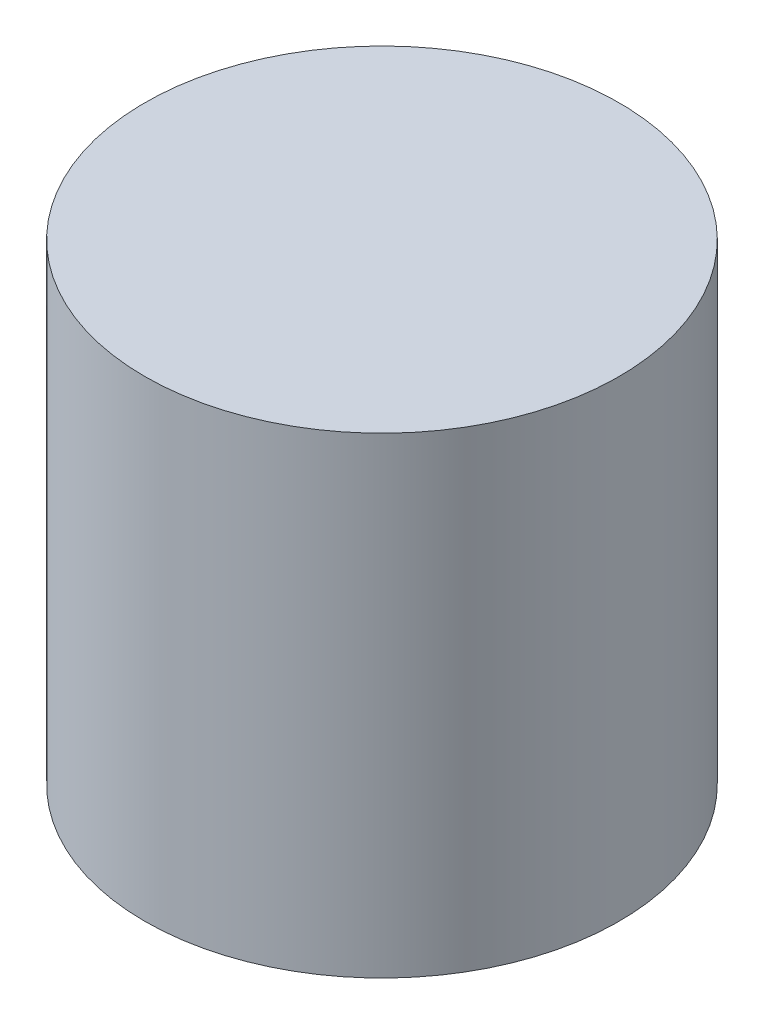
SolidWorks part; units mm, degrees
ref_plane "Front Plane" through (0, 0, 0) normal (0, 0, 1) x (1, 0, 0)
ref_plane "Top Plane" through (0, 0, 0) normal (0, 1, 0) x (1, 0, 0)
ref_plane "Right Plane" through (0, 0, 0) normal (1, 0, 0) x (0, 0, -1)
sketch "Sketch1" plane through (0, 0, 0) normal (0, 1, 0) x (1, 0, 0)
  circle A0 centre (0, 0) radius 39.5
  dimension "D1" = 79
extrude "Boss-Extrude1" add sketch "Sketch1" along normal blind 33.9
sketch "Sketch6" plane through (0, 0, 0) normal (0, 1, 0) x (1, 0, 0)
  line L0 (0, 0) -> (34, 0) construction
  line L1 (29.7371, 12.56) -> (-29.7371, 12.56)
  line L5 (0, 12.56) -> (0, 0) construction
  line L6 (29.7371, -12.56) -> (-29.7371, -12.56)
  circle A0 centre (0, 0) radius 33.7 construction
  circle A1 centre (0, 0) radius 39.5 construction
  arc A3 (29.7371, 12.56) -> (29, 17.1665) centre (23.5311, 13.9292) ccw
  arc A4 (29, 17.1665) -> (29, -17.1665) centre (0, 0) cw
  arc A5 (29.7371, -12.56) -> (29, -17.1665) centre (23.5311, -13.9292) cw
  arc A6 (-29.7371, -12.56) -> (-29, -17.1665) centre (-23.5311, -13.9292) ccw
  arc A7 (-29, 17.1665) -> (-29, -17.1665) centre (0, 0) ccw
  arc A8 (-29.7371, 12.56) -> (-29, 17.1665) centre (-23.5311, 13.9292) cw
  point P15 (0, -12.56)
  point P20 (28.514, 9)
  dimension "D1" = 5.8
  dimension "D2" = 12.56
  dimension "D3" = 6.3552
  dimension "D4" = 29
extrude "Boss-Extrude3" add sketch "Sketch6" against normal blind 13.7
sketch "Sketch7" plane through (0, 0, 0) normal (0, 1, 0) x (1, 0, 0)
  circle A5 centre (0, 0) radius 39.5
  circle A6 centre (0, 0) radius 34
  dimension "D1" = 5.5
  dimension "D2" = 79
extrude "Boss-Extrude4" add sketch "Sketch7" against normal blind 44.7
sketch "Sketch8" plane through (0, 0, 0) normal (0, 1, 0) x (1, 0, 0)
  line L0 (-29.7371, -12.56) -> (29.7371, -12.56) construction
  line L1 (0, -12.56) -> (0, -34) construction
  line L2 (-29.7371, -12.56) -> (29.7371, -12.56) construction
  circle A0 centre (0, -23.44) radius 8
  circle A3 centre (12.5, -26.56) radius 2.75
  circle A4 centre (20, -19.06) radius 4.9
  circle A5 centre (0, 0) radius 34 construction
  circle A6 centre (-12.5, -26.56) radius 2.75
  circle A7 centre (-20, -19.06) radius 4.9
  dimension "D1" = 16
  dimension "D2" = 9.8
  dimension "D3" = 5.5
  dimension "D4" = 6.5
  dimension "D5" = 20
  dimension "D6" = 12.5
  dimension "D7" = 14
  dimension "D8" = 10.88
extrude "Cut-Extrude2" cut sketch "Sketch8" along normal blind 19
